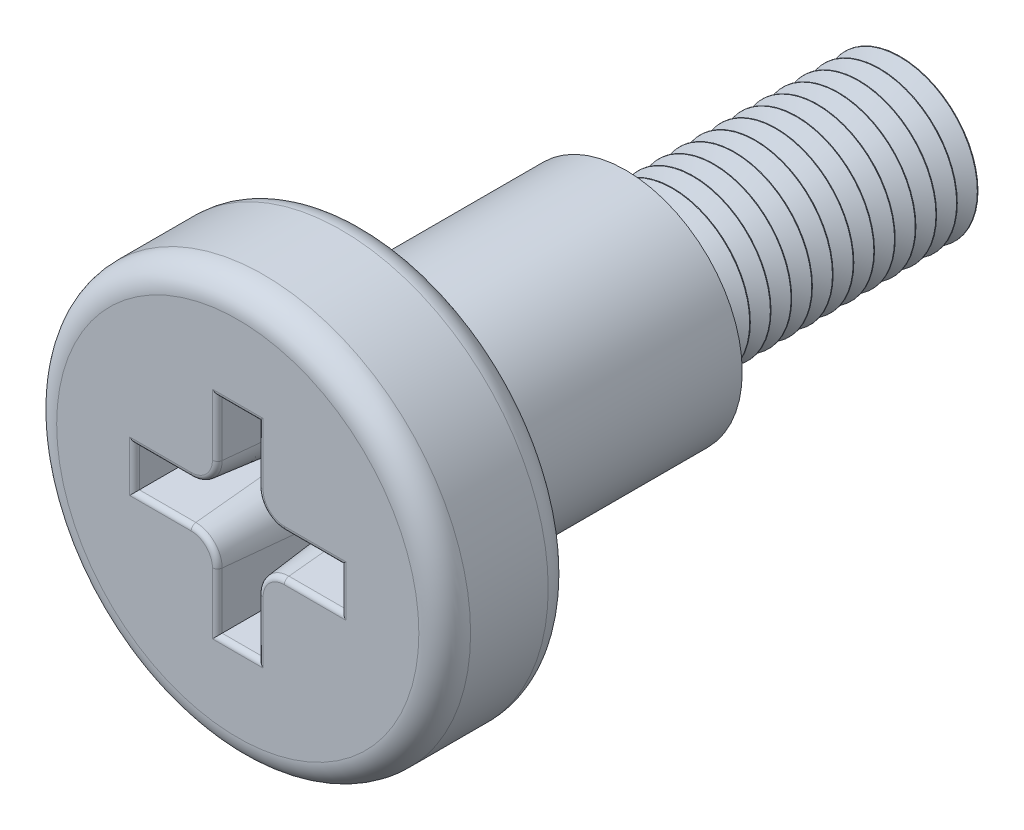
SolidWorks part; units mm, degrees
ref_plane "Front Plane" through (0, 0, 0) normal (0, 0, 1) x (1, 0, 0)
ref_plane "Top Plane" through (0, 0, 0) normal (0, 1, 0) x (1, 0, 0)
ref_plane "Right Plane" through (0, 0, 0) normal (1, 0, 0) x (0, 0, -1)
sketch "Sketch1" plane through (0, 0, 0) normal (0, 0, 1) x (1, 0, 0)
  circle A0 centre (0, 0) radius 4
  dimension "D1" = 8
extrude "Boss-Extrude1" add sketch "Sketch1" along normal blind 2.5
fillet "Fillet1" radius 0.5 2 edges at (4, 0, 0) (4, 0, 2.5)
sketch "Sketch2" plane through (0, 0, 0) normal (0, 0, -1) x (-1, 0, 0)
  circle A0 centre (0, 0) radius 2.25
  dimension "D1" = 4.5
extrude "Boss-Extrude2" add sketch "Sketch2" along normal blind 5
sketch "Sketch3" plane through (0, 0, -5) normal (0, 0, -1) x (-1, 0, 0)
  circle A0 centre (0, 0) radius 1.5
  dimension "D1" = 3
extrude "Boss-Extrude3" add sketch "Sketch3" along normal blind 5.5
sketch "Sketch4" plane through (0, 0, 2.5) normal (0, 0, 1) x (1, 0, 0)
  line L1 (-0.4, -2) -> (0.4, -2)
  line L2 (-0.4, -2) -> (-0.4, -0.9)
  line L3 (-0.4, 2) -> (0.4, 2)
  line L4 (0.4, -2) -> (0.4, -0.9)
  line L5 (-0.4, -2) -> (0.4, 2) construction
  line L6 (-0.4, 2) -> (0.4, -2) construction
  line L7 (-2, -0.4) -> (-0.9, -0.4)
  line L8 (-2, -0.4) -> (-2, 0.4)
  line L9 (-2, 0.4) -> (-0.9, 0.4)
  line L10 (2, -0.4) -> (2, 0.4)
  line L11 (-2, -0.4) -> (2, 0.4) construction
  line L12 (-2, 0.4) -> (2, -0.4) construction
  line L13 (-0.4, 0.9) -> (-0.4, 2)
  line L14 (0.9, -0.4) -> (2, -0.4)
  line L15 (0.4, 0.9) -> (0.4, 2)
  line L16 (0.9, 0.4) -> (2, 0.4)
  arc A0 (0.4, 0.9) -> (0.9, 0.4) centre (0.9, 0.9) ccw
  arc A1 (0.9, -0.4) -> (0.4, -0.9) centre (0.9, -0.9) ccw
  arc A2 (-0.4, -0.9) -> (-0.9, -0.4) centre (-0.9, -0.9) ccw
  arc A3 (-0.9, 0.4) -> (-0.4, 0.9) centre (-0.9, 0.9) ccw
  point P0 (0, 0)
  point P6 (0, 0)
  point P23 (-0.4, 0.4)
  dimension "D5" = 0.5
  dimension "D1" = 0.8
  dimension "D2" = 0.8
  dimension "D3" = 4
  dimension "D4" = 4
extrude "Cut-Extrude1" cut sketch "Sketch4" against normal blind 2 draft 6
fillet "Fillet2" radius 0.1 16 edges at (0, 2, 2.5) (-0.4, 1.45, 2.5) (-0.5464, 0.5464, 2.5) (-1.45, 0.4, 2.5) (-2, 0, 2.5) (-1.45, -0.4, 2.5) (-0.5464, -0.5464, 2.5) (-0.4, -1.45, 2.5) (0, -2, 2.5) (0.4, -1.45, 2.5) (0.5464, -0.5464, 2.5) (1.45, -0.4, 2.5) (2, 0, 2.5) (1.45, 0.4, 2.5) (0.5464, 0.5464, 2.5) (0.4, 1.45, 2.5)
sketch "Sketch5" plane through (0, 0, 0) normal (1, 0, 0) x (0, 0, -1)
  line L0 (10.5, 1.2) -> (10.7, 1.51)
  line L1 (10.5, -1.5) -> (10.5, 1.5) construction
  line L2 (10.7, 1.51) -> (10.3, 1.51)
  line L3 (10.3, 1.51) -> (10.5, 1.2)
  line L4 (10.5, 1.5) -> (5, 1.5) construction
  line L5 (-3.2905, 0) -> (14.2005, 0) construction
  dimension "D1" = 0.3
  dimension "D2" = 0.4
  dimension "D3" = 0.2
  dimension "D4" = 0.31
revolve "Cut-Revolve1" cut sketch "Sketch5" angle 360 about L5
sketch "Sketch6" plane through (0, 0, 0) normal (1, 0, 0) x (0, 0, -1)
  line L0 (-4.8442, 0) -> (14.4511, 0) construction
pattern_linear "LPattern1" count 14 spacing 0.4 along (0, 0, 1) of "Cut-Revolve1"
